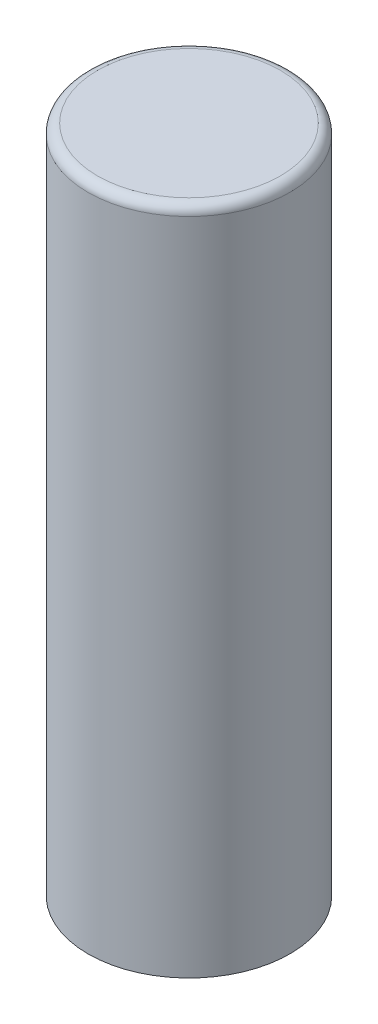
SolidWorks part; units mm, degrees
ref_plane "Front Plane" through (0, 0, 0) normal (0, 0, 1) x (1, 0, 0)
ref_plane "Top Plane" through (0, 0, 0) normal (0, 1, 0) x (1, 0, 0)
ref_plane "Right Plane" through (0, 0, 0) normal (1, 0, 0) x (0, 0, -1)
sketch "Sketch2" plane through (0, 0, 0) normal (0, 1, 0) x (1, 0, 0)
  circle A0 centre (0, 0) radius 10.61
  dimension "D1" = 21.22
extrude "Boss-Extrude1" add sketch "Sketch2" along normal blind 70.3
fillet "Fillet1" radius 1 1 edges at (0, 70.3, 10.61)
